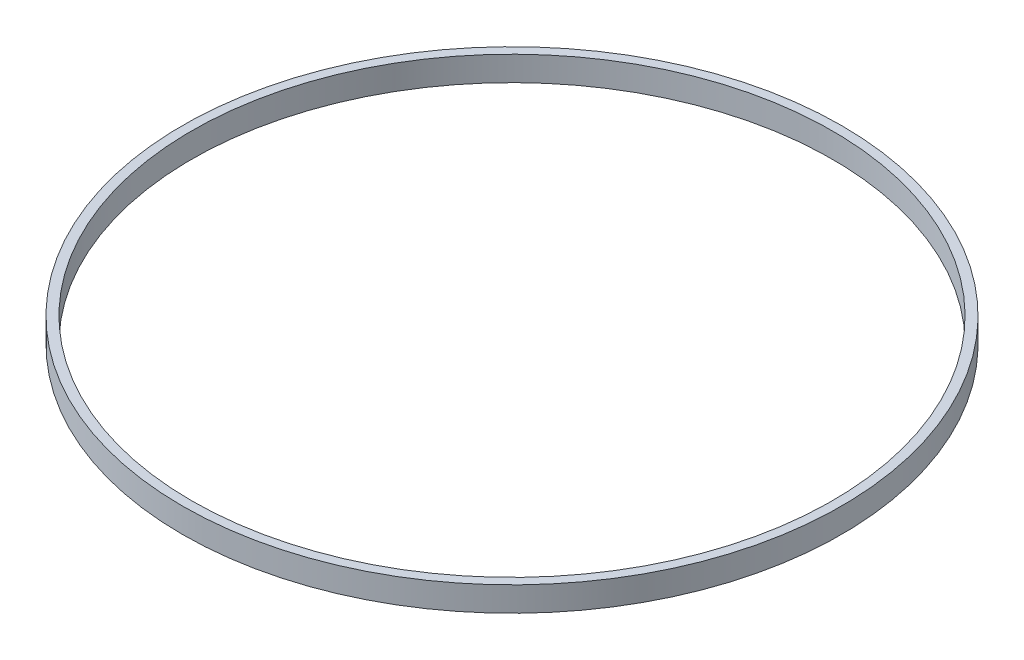
SolidWorks part; units mm, degrees
ref_plane "Front Plane" through (0, 0, 0) normal (0, 0, 1) x (1, 0, 0)
ref_plane "Top Plane" through (0, 0, 0) normal (0, 1, 0) x (1, 0, 0)
ref_plane "Right Plane" through (0, 0, 0) normal (1, 0, 0) x (0, 0, -1)
ref_plane "Plane4" through (0, 0, 0) normal (0, 0, -1) x (-1, 0, 0)
sketch "Sketch1" plane through (0, 0, 0) normal (0, 0, -1) x (-1, 0, 0)
  line L0 (-58.2, 0.2044) -> (-56.58, 0.2044)
  line L2 (-56.58, 0.2044) -> (-56.58, 4.5544)
  line L4 (-56.58, 4.5544) -> (-58.2, 4.5544)
  line L5 (-58.2, 4.5544) -> (-58.2, 0.2044)
  line L6 (0, 0) -> (0, 4.35) construction
  dimension "D1" = 1.62
  dimension "D2" = 58.2
  dimension "D3" = 4.35
revolve "Revolve1" add sketch "Sketch1" angle 360 about L6
